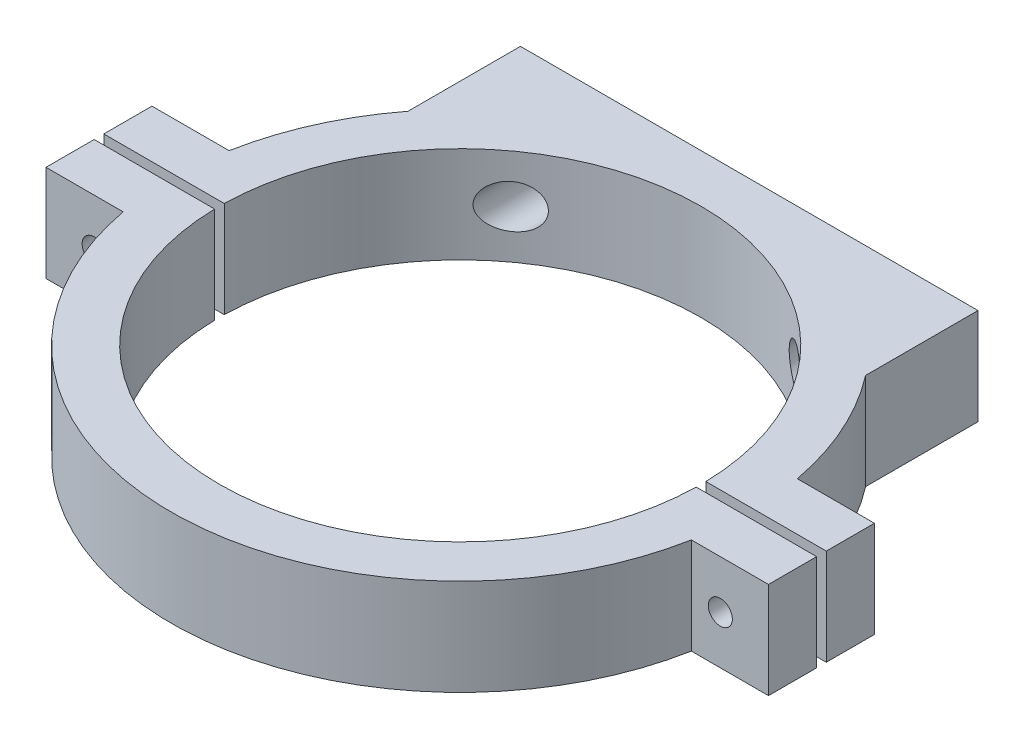
SolidWorks part; units mm, degrees
ref_plane "Front Plane" through (0, 0, 0) normal (0, 0, 1) x (1, 0, 0)
ref_plane "Top Plane" through (0, 0, 0) normal (0, 1, 0) x (1, 0, 0)
ref_plane "Right Plane" through (0, 0, 0) normal (1, 0, 0) x (0, 0, -1)
sketch "Sketch1" plane through (0, 0, 0) normal (0, 1, 0) x (1, 0, 0)
  line L0 (0, 0) -> (-135.0958, 0) construction
  line L1 (-47.5, 84.7635) -> (-47.5, -91.9146) construction
  line L2 (47.5, 84.7635) -> (47.5, -87.7205) construction
  line L3 (-47.5, 60) -> (47.5, 60)
  line L4 (47.5, 60) -> (47.5, 36.6572)
  line L5 (-47.5, 60) -> (-47.5, 36.6572)
  line L6 (75.1064, 11) -> (-59.9895, 11) construction
  line L7 (76.0594, -11) -> (-59.0364, -11) construction
  line L8 (-75, 11) -> (-75, 1)
  line L9 (-75, -11) -> (-58.983, -11)
  line L10 (-75, 11) -> (-58.983, 11)
  line L11 (58.983, 11) -> (75, 11)
  line L12 (75, 11) -> (75, 1)
  line L13 (75, -11) -> (58.983, -11)
  line L14 (-75, 1) -> (-49.99, 1)
  line L15 (-75, -1) -> (-49.99, -1)
  line L16 (-75, -1) -> (-75, -11)
  line L17 (75, -1) -> (75, -11)
  line L18 (49.99, -1) -> (75, -1)
  line L19 (49.99, 1) -> (75, 1)
  arc A0 (-49.99, -1) -> (49.99, -1) centre (0, 0) ccw
  arc A1 (-47.5, 36.6572) -> (-58.983, 11) centre (0, 0) ccw
  arc A2 (-58.983, -11) -> (58.983, -11) centre (0, 0) ccw
  arc A3 (49.99, 1) -> (-49.99, 1) centre (0, 0) ccw
  arc A4 (58.983, 11) -> (47.5, 36.6572) centre (0, 0) ccw
  dimension "D1" = 100
  dimension "D2" = 120
  dimension "D3" = 47.5
  dimension "D4" = 47.5
  dimension "D5" = 11
  dimension "D6" = 11
  dimension "D7" = 1
  dimension "D8" = 1
  dimension "D9" = 150
  dimension "D10" = 75
extrude "Boss-Extrude1" add sketch "Sketch1" along normal blind 20
sketch "Sketch2" plane through (0, 0, -60) normal (0, 0, -1) x (-1, 0, 0)
  line L0 (0, 20) -> (0, 5) construction
  line L3 (-9.3292, 10) -> (25.2347, 10) construction
  line L4 (47.5, 20) -> (47.5, 0) construction
  line L5 (-75, 0) -> (-58.983, 0) construction
  circle A0 centre (-29.5, 10) radius 2.5
  circle A1 centre (29.5, 10) radius 2.5
  dimension "D1" = 29.5
  dimension "D2" = 29.5
  dimension "D3" = 47.5
  dimension "D4" = 10
extrude "Cut-Extrude1" cut sketch "Sketch2" against normal blind 50
ref_plane "Plane1" through (0, 0, -50) normal (0, 0, -1) x (-1, 0, 0)
sketch "Sketch4" plane through (0, 0, -50) normal (0, 0, -1) x (-1, 0, 0)
  line L0 (58.983, 20) -> (-58.983, 20) construction
  line L1 (-47.5, 0) -> (47.5, 0) construction
  circle A0 centre (-29.5, 10) radius 4.5
  circle A1 centre (29.5, 10) radius 4.5
  point P4 (0, 20)
  point P6 (-36.6835, 6.573)
  dimension "D1" = 59
  dimension "D2" = 29.5
  dimension "D3" = 10
extrude "Cut-Extrude2" cut sketch "Sketch4" against normal blind 50
sketch "Sketch5" plane through (0, 0, -11) normal (0, 0, -1) x (-1, 0, 0)
  line L0 (-75, 20) -> (-75, 0) construction
  line L1 (75, 20) -> (75, 0) construction
  line L2 (-75, 0) -> (-58.983, 0) construction
  line L3 (58.983, 0) -> (75, 0) construction
  circle A0 centre (-65, 10) radius 2
  circle A1 centre (65, 10) radius 2
  dimension "D1" = 10
  dimension "D2" = 10
  dimension "D3" = 10
  dimension "D4" = 10
extrude "Cut-Extrude3" cut sketch "Sketch5" against normal blind 10
cosmetic thread "Cosmetic Thread1" parameters "D1"=5, "D2"=5
cosmetic thread "Cosmetic Thread2" parameters "D1"=5, "D2"=5
sketch "Sketch6" plane through (0, 0, 11) normal (0, 0, 1) x (1, 0, 0)
  line L0 (58.983, 0) -> (75, 0) construction
  line L1 (-75, 0) -> (-58.983, 0) construction
  line L2 (75, 20) -> (75, 0) construction
  line L3 (-75, 20) -> (-75, 0) construction
  circle A0 centre (65, 10) radius 2.5
  circle A1 centre (-65, 10) radius 2.5
  point P4 (66.9915, 0)
  dimension "D1" = 10
  dimension "D2" = 10
  dimension "D3" = 10
  dimension "D4" = 10
extrude "Cut-Extrude4" cut sketch "Sketch6" against normal blind 10
